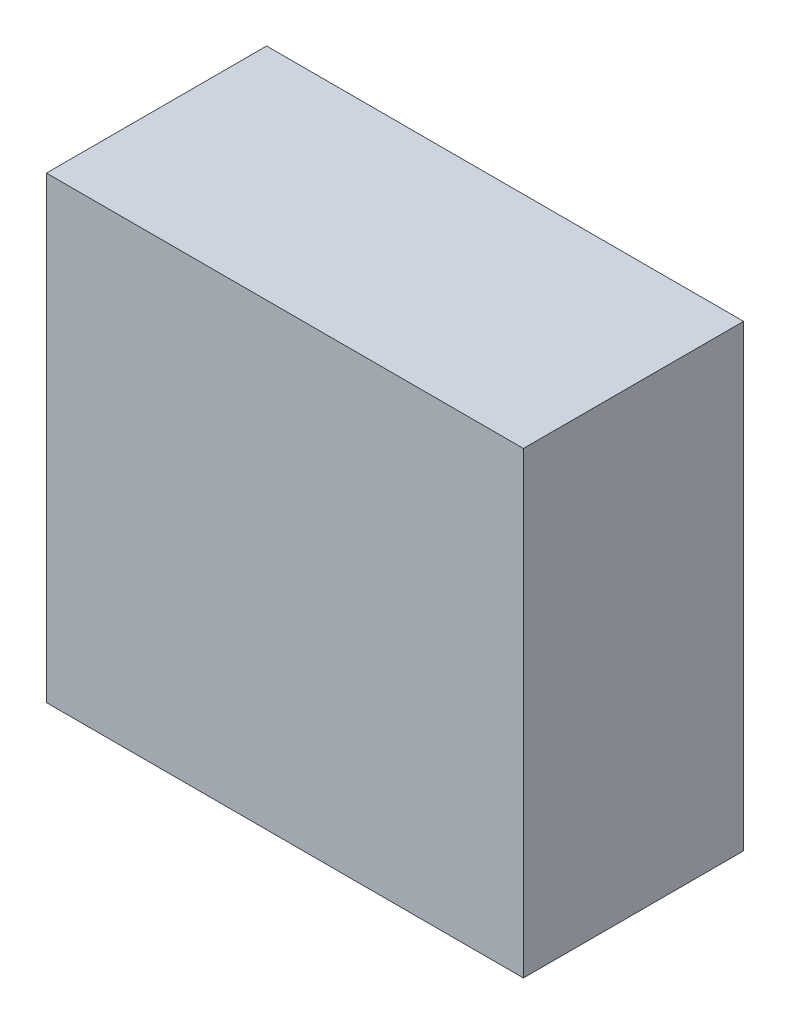
SolidWorks part; units mm, degrees
ref_plane "Front Plane" through (0, 0, 0) normal (0, 0, 1) x (1, 0, 0)
ref_plane "Top Plane" through (0, 0, 0) normal (0, 1, 0) x (1, 0, 0)
ref_plane "Right Plane" through (0, 0, 0) normal (1, 0, 0) x (0, 0, -1)
other "Configuration Table"
sketch "Sketch1" plane through (0, 0, 0) normal (0, 0, 1) x (1, 0, 0)
  line L1 (700, 1690) -> (830, 1690)
  line L2 (700, 1690) -> (700, 1815)
  line L3 (700, 1815) -> (830, 1815)
  line L4 (830, 1690) -> (830, 1815)
extrude "STORE_pano_guc_kaynagi_24V_10A_1" add sketch "Sketch1" against normal blind 60 from offset 640 separate body
